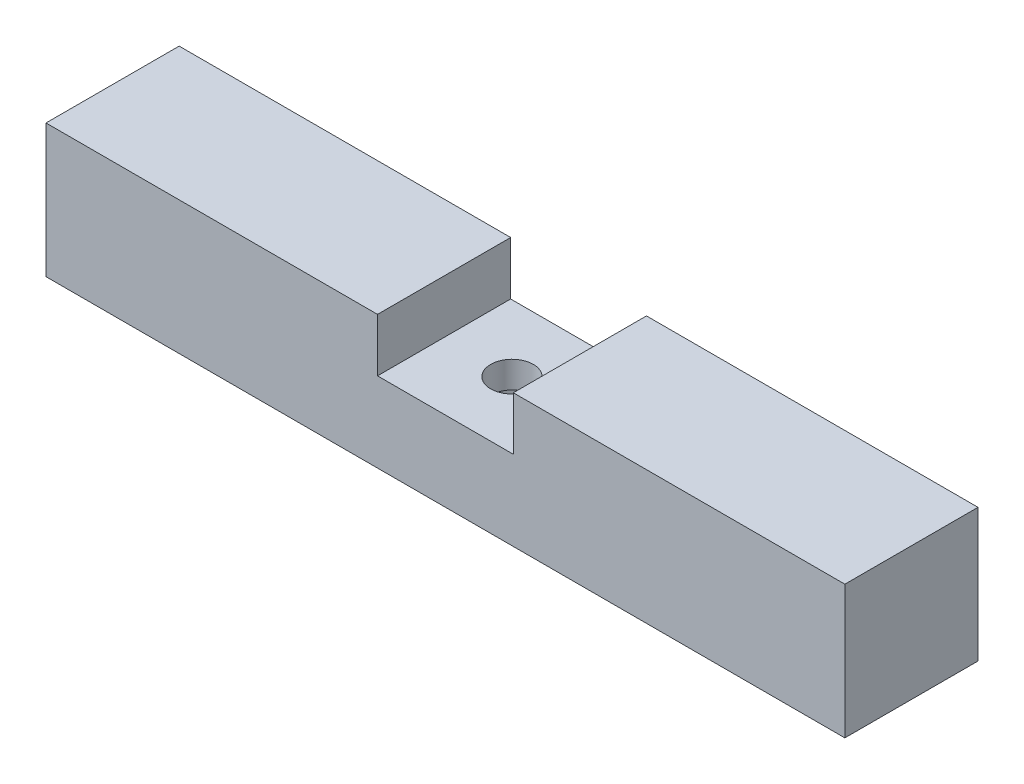
SolidWorks part; units mm, degrees
ref_plane "Front Plane" through (0, 0, 0) normal (0, 0, 1) x (1, 0, 0)
ref_plane "Top Plane" through (0, 0, 0) normal (0, 1, 0) x (1, 0, 0)
ref_plane "Right Plane" through (0, 0, 0) normal (1, 0, 0) x (0, 0, -1)
sketch "Sketch1" plane through (0, 0, 0) normal (0, 0, 1) x (1, 0, 0)
  line L0 (-5.1, 10) -> (-5.1, 6)
  line L1 (-30, 0) -> (30, 0)
  line L2 (-30, 0) -> (-30, 10)
  line L3 (-30, 10) -> (-5.1, 10)
  line L4 (30, 0) -> (30, 10)
  line L5 (-5.1, 6) -> (5.1, 6)
  line L6 (5.1, 6) -> (5.1, 10)
  line L7 (5.1, 10) -> (30, 10)
  point P4 (0, 0)
  point P8 (0, 6)
  dimension "D1" = 10
  dimension "D2" = 60
  dimension "D3" = 4
  dimension "D4" = 10.2
extrude "Boss-Extrude1" add sketch "Sketch1" along normal blind 10
sketch "Sketch2" plane through (0, 6, 0) normal (0, 1, 0) x (1, 0, 0)
  line L0 (-5.1, 0) -> (5.1, -10) construction
  circle A0 centre (0, -5) radius 1.6
  dimension "D1" = 3.2
extrude "Cut-Extrude1" cut sketch "Sketch2" against normal blind 10
sketch "Sketch3" plane through (0, 0, 0) normal (0, -1, 0) x (1, 0, 0)
  circle A0 centre (0, 5) radius 3
  dimension "D1" = 6
extrude "Cut-Extrude2" cut sketch "Sketch3" against normal blind 4
